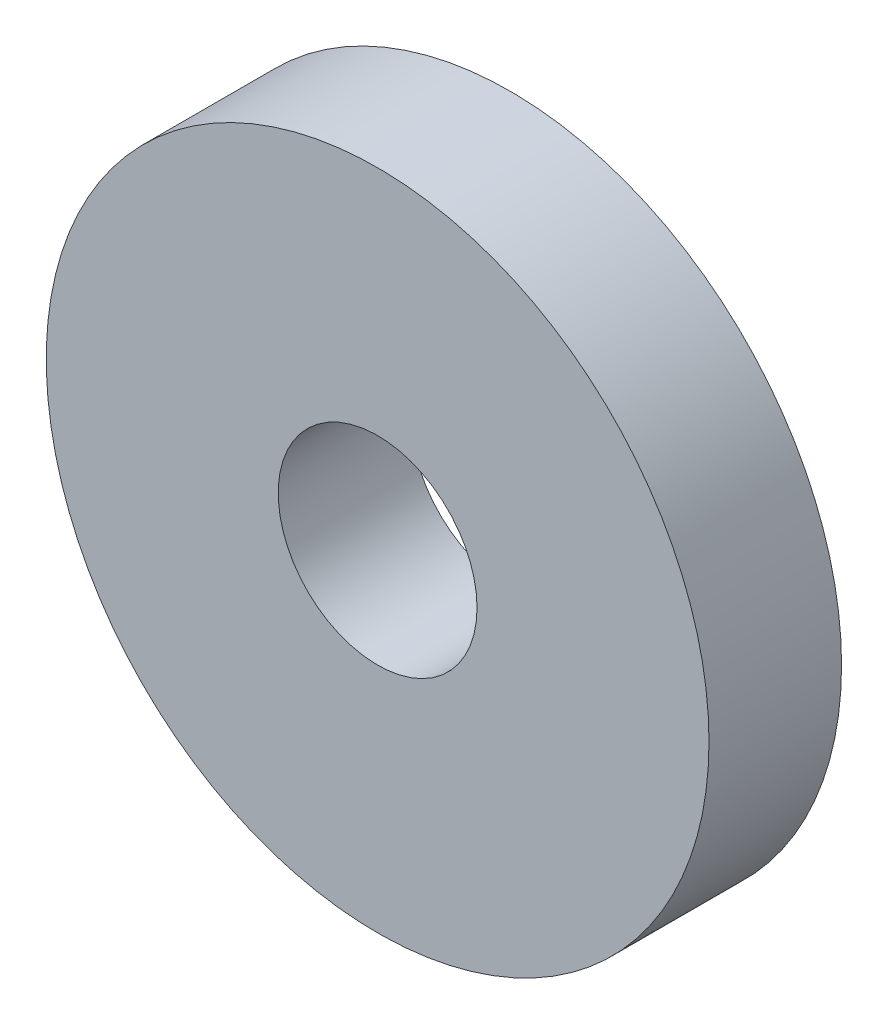
SolidWorks part; units mm, degrees
ref_plane "Front Plane" through (0, 0, 0) normal (0, 0, 1) x (1, 0, 0)
ref_plane "Top Plane" through (0, 0, 0) normal (0, 1, 0) x (1, 0, 0)
ref_plane "Right Plane" through (0, 0, 0) normal (1, 0, 0) x (0, 0, -1)
sketch "Sketch1" plane through (0, 0, 0) normal (0, 0, 1) x (1, 0, 0)
  circle A0 centre (4.3795, -5.5785) radius 1.5
  circle A1 centre (4.3795, -5.5785) radius 5
  dimension "D1" = 3
  dimension "D2" = 10
extrude "Boss-Extrude1" add sketch "Sketch1" along normal blind 2
